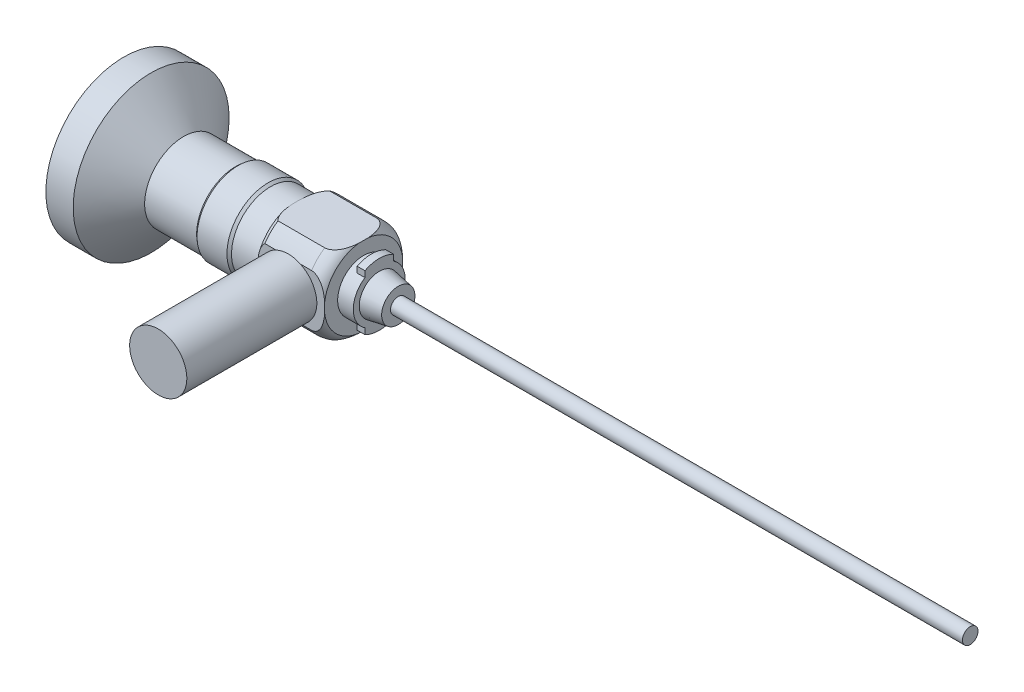
SolidWorks part; units mm, degrees
ref_plane "Front Plane" through (0, 0, 0) normal (0, 0, 1) x (1, 0, 0)
ref_plane "Top Plane" through (0, 0, 0) normal (0, 1, 0) x (1, 0, 0)
ref_plane "Right Plane" through (0, 0, 0) normal (1, 0, 0) x (0, 0, -1)
ref_axis "Axis1" through (88.99, 0, 0) along (-1, 0, 0)
sketch "Sketch1" plane through (0, 0, 0) normal (0, 0, 1) x (1, 0, 0)
  line L0 (-74.5697, 0) -> (-77.8697, -15) construction
  line L1 (-77.8697, -15) -> (-72.6197, -15)
  line L2 (-72.6197, -15) -> (-66.3697, -7.5)
  line L3 (-66.3697, -7.5) -> (-56.3697, -7.5)
  line L4 (-56.3697, -7.5) -> (-55.8897, -7.9)
  line L5 (-55.8897, -7.9) -> (-50.1397, -7.9)
  line L6 (-50.1397, -7.9) -> (-49.6597, -7.5)
  line L7 (-49.6597, -7.5) -> (-44.6597, -7.5)
  line L8 (88.99, 0) -> (-88.99, 0) construction
  line L9 (-74.5697, 0) -> (-25.0835, 0)
  line L10 (-43.2452, -9) -> (-34.2597, -9)
  line L11 (-31.7461, -7.5592) -> (-31.7461, -5)
  line L12 (-31.7461, -5) -> (-30.2461, -5)
  line L13 (-30.2461, -5) -> (-30.2461, -6)
  line L14 (-30.2461, -6) -> (-28.7461, -6)
  line L15 (-28.7461, -6) -> (-28.7461, -3.85)
  line L16 (-28.7461, -3.85) -> (-25.0835, -3.2)
  line L17 (-25.0835, -3.2) -> (-25.0835, 0)
  arc A0 (-74.5697, 0) -> (-77.8697, -15) centre (-129.3209, 4.1823) cw
  arc A1 (-44.6597, -7.5) -> (-40.5597, -9) centre (-41.9025, -6.3168) ccw
  arc A2 (-34.2597, -9) -> (-31.7461, -7.5592) centre (-34.3096, -6) ccw
  point P12 (-40.5597, -9)
  point P16 (-34.2597, -9)
  point P17 (-44.6597, -9)
  point P18 (-37.4097, -9)
  point P20 (-30.1597, -9)
  dimension "D4" = 11.5
  dimension "D12" = 9
  dimension "D13" = 3.15
  dimension "D15" = 5
  dimension "D1" = 5.25
  dimension "D2" = 15
  dimension "D3" = 3.3
  dimension "D5" = 7.5
  dimension "D6" = 5.75
  dimension "D7" = 7.9
  dimension "D8" = 7.5
  dimension "D9" = 10
  dimension "D10" = 5
  dimension "D11" = 14.5
  dimension "D14" = 3.15
  dimension "D16" = 6
  dimension "D17" = 1.5
  dimension "D18" = 1.5
  dimension "D19" = 3.85
  dimension "D20" = 3.2
revolve "Revolve1" add sketch "Sketch1" angle 360 about axis through (88.99, 0, 0) along (-1, 0, 0)
sketch "Sketch2" plane through (-31.7461, 0, 0) normal (1, 0, 0) x (0, 0, -1)
  line L0 (0, 9) -> (0, -9)
  line L1 (12.4327, -7.5) -> (-12.4327, -7.5)
  line L2 (12.4327, -7.5) -> (12.4327, 7.5) construction
  line L3 (12.4327, 7.5) -> (-12.4327, 7.5)
  line L4 (-12.4327, -7.5) -> (-12.4327, 7.5) construction
  line L5 (12.4327, 7.5) -> (-12.4327, -7.5) construction
  line L6 (12.4327, 7.5) -> (12.4327, 11.5013)
  line L7 (12.4327, 11.5013) -> (-12.4327, 11.5013)
  line L8 (-12.4327, 11.5013) -> (-12.4327, 7.5)
  line L9 (-12.4327, -7.5) -> (-12.4327, -12.9232)
  line L10 (-12.4327, -12.9232) -> (12.4327, -12.9232)
  line L11 (12.4327, -12.9232) -> (12.4327, -7.5)
  circle A0 centre (0, 0) radius 9 construction
  circle A1 centre (0, 0) radius 9
  dimension "D1" = 15
extrude "Cut-Extrude1" cut sketch "Sketch2" against normal blind 15 contours L9 L10 L11 L1 | L8 L3 L6 L7
pattern_circular "CirPattern1" count 2 every 90 about axis through (88.99, 0, 0) along (-1, 0, 0) of "Cut-Extrude1"
sketch "Sketch3" plane through (-28.7461, 0, 0) normal (1, 0, 0) x (0, 0, -1)
  line L0 (2.75, 6.4372) -> (2.75, -6.4372) construction
  line L1 (-2.75, -6.4372) -> (-2.75, 6.4372) construction
  line L2 (2.75, -6.4372) -> (-2.75, 6.4372) construction
  line L3 (2.75, -4.1758) -> (2.75, -6.4372)
  line L4 (2.75, -6.4372) -> (-2.75, -6.4372) construction
  line L5 (-2.75, -6.4372) -> (-2.75, -4.1758)
  line L6 (2.75, 4.1758) -> (2.75, 6.4372)
  line L7 (2.75, 6.4372) -> (-2.75, 6.4372) construction
  line L8 (-2.75, 6.4372) -> (-2.75, 4.1758)
  line L9 (2.75, 6.4372) -> (6.4302, 6.4372)
  line L10 (6.4302, 6.4372) -> (5.9638, -6.4372)
  line L11 (5.9638, -6.4372) -> (2.75, -6.4372)
  line L12 (-2.75, -6.4372) -> (-6.2806, -6.4372)
  line L13 (-6.2806, -6.4372) -> (-6.2806, 6.4372)
  line L14 (-6.2806, 6.4372) -> (-2.75, 6.4372)
  circle A0 centre (0, 0) radius 6 construction
  circle A1 centre (0, 0) radius 6 construction
  arc A2 (2.75, -4.1758) -> (2.75, 4.1758) centre (0, 0) ccw
  arc A3 (-2.75, 4.1758) -> (-2.75, -4.1758) centre (0, 0) ccw
  point P3 (7, 0)
  point P4 (0, 0)
  dimension "D1" = 10
  dimension "D3" = 5.5
extrude "Cut-Extrude2" cut sketch "Sketch3" against normal up to surface (1.5 mm away) up to face at (-30.2461, 0, -6)
sketch "Sketch4" plane through (0, 0, 7.5) normal (0, 0, 1) x (1, 0, 0)
  line L0 (-34.2597, 4.9749) -> (-43.2452, -4.9749) construction
  circle A0 centre (-38.7525, 0) radius 5.5
  dimension "D1" = 11
extrude "Boss-Extrude1" add sketch "Sketch4" along normal blind 25
sketch "Sketch5" plane through (-25.0835, 0, 0) normal (1, 0, 0) x (0, 0, -1)
  circle A0 centre (0, 0) radius 1.5
  dimension "D1" = 3
extrude "Boss-Extrude2" add sketch "Sketch5" along normal blind 110
